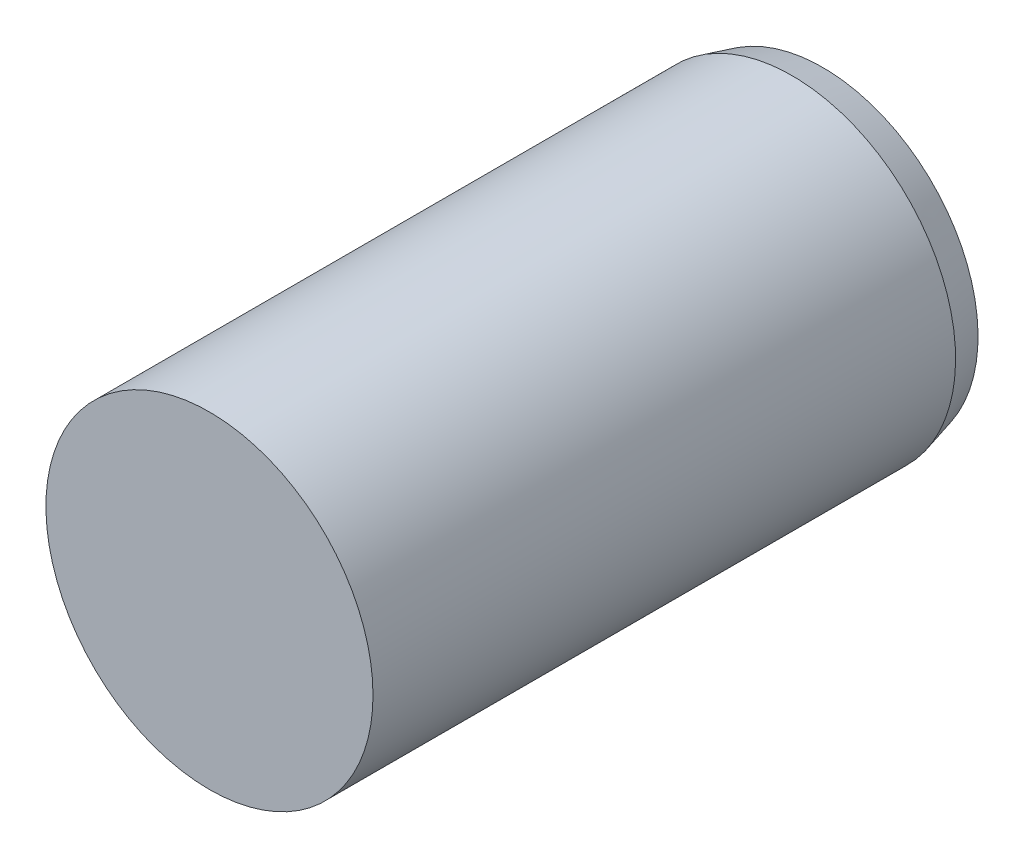
SolidWorks part; units mm, degrees
material "416 SS"
ref_plane "Front Plane" through (0, 0, 0) normal (0, 0, 1) x (1, 0, 0)
ref_plane "Top Plane" through (0, 0, 0) normal (0, 1, 0) x (1, 0, 0)
ref_plane "Right Plane" through (0, 0, 0) normal (1, 0, 0) x (0, 0, -1)
sketch "Sketch1" plane through (0, 0, 0) normal (1, 0, 0) x (0, 0, -1)
  line L0 (-6.35, 0) -> (6.35, 0) construction
  point P2 (0, 0)
  dimension "Length" = 12.7
sketch "Sketch2" plane through (0, 0, 0) normal (0, 0, 1) x (1, 0, 0)
  circle A0 centre (0, 0) radius 3.175
  point P3 (0, 3.175)
  dimension "Diameter" = 6.35
sketch "Sketch3" plane through (0, 0, 0) normal (1, 0, 0) x (0, 0, -1)
  line L0 (-6.35, 2.3812) -> (-5.5562, 3.175)
  line L1 (-6.35, 0) -> (6.35, 0)
  line L2 (-6.35, 0) -> (-6.35, 2.3812)
  line L3 (-5.5562, 3.175) -> (5.7547, 3.175)
  line L4 (6.35, 0) -> (6.35, 3.0155)
  line L5 (6.35, 3.0155) -> (5.7547, 3.175)
  dimension "D1" = 45
  dimension "D2" = 0.7937
  dimension "D3" = 15
  dimension "D4" = 0.5953
revolve "Revolve1" add sketch "Sketch3" angle 360 about L1
sketch "Sketch4" plane through (0, 0, 6.35) normal (0, 0, 1) x (1, 0, 0)
  circle A1 centre (0, 0) radius 3.175
  circle A2 centre (0, 0) radius 3.175
  dimension "D1" = 0
extrude "Cut-Extrude1" cut sketch "Sketch4" against normal blind 0.7937
equation "\"D2@Sketch3\"=0.125*\"Diameter@Sketch2\""
equation "\"D4@Sketch3\"=0.75*\"D2@Sketch3\""
